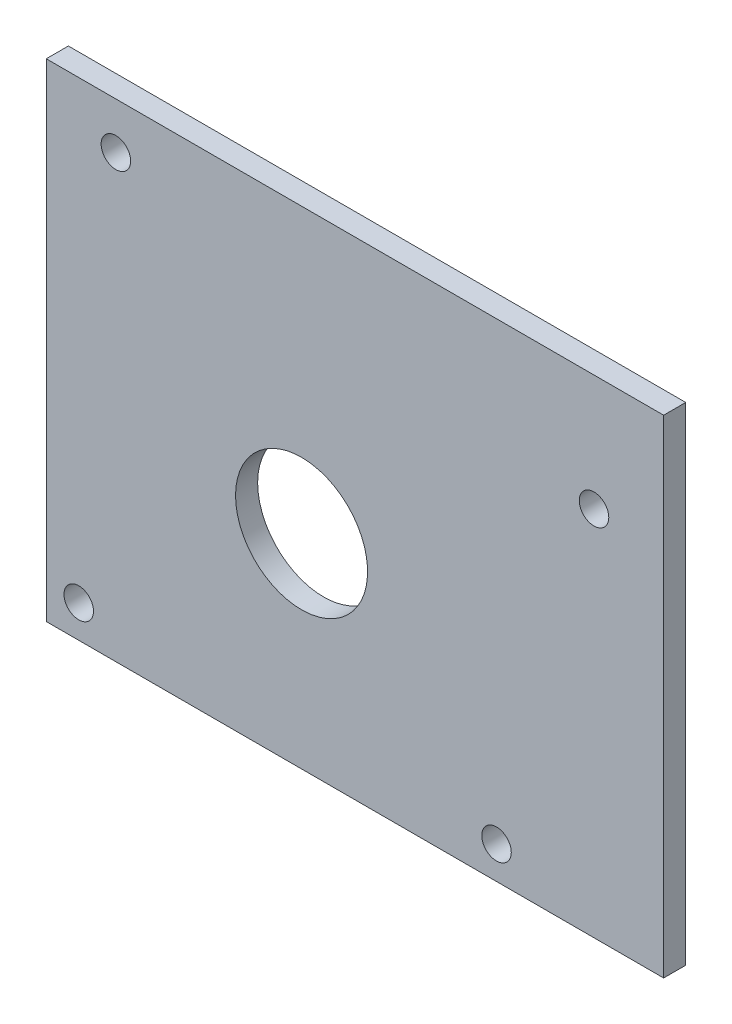
SolidWorks part; units mm, degrees
ref_plane "Front Plane" through (0, 0, 0) normal (0, 0, 1) x (1, 0, 0)
ref_plane "Top Plane" through (0, 0, 0) normal (0, 1, 0) x (1, 0, 0)
ref_plane "Right Plane" through (0, 0, 0) normal (1, 0, 0) x (0, 0, -1)
sketch "Sketch1" plane through (0, 0, 0) normal (0, 0, 1) x (1, 0, 0)
  line L0 (-85.0355, 74.3413) -> (-85.0355, -30.6587)
  line L1 (-85.0355, 74.3413) -> (47.9645, 74.3413)
  line L2 (-85.0355, -30.6587) -> (47.9645, -30.6587)
  line L3 (47.9645, 74.3413) -> (47.9645, -30.6587)
  circle A0 centre (-30.0355, 13.2613) radius 14.225
  dimension "D3" = 55
  dimension "D5" = 43.92
  dimension "D1" = 105
  dimension "D2" = 133
extrude "Boss-Extrude2" add sketch "Sketch1" along normal blind 4.7625
sketch "Sketch2" plane through (0, 0, 4.7625) normal (0, 0, 1) x (1, 0, 0)
  line L1 (-85.0355, 74.3413) -> (-85.0355, -30.6587) construction
  line L2 (47.9645, 74.3413) -> (-85.0355, 74.3413) construction
  line L3 (47.9645, -30.6587) -> (47.9645, 74.3413) construction
  line L4 (-85.0355, -30.6587) -> (47.9645, -30.6587) construction
  circle A1 centre (-70.0355, 64.3413) radius 3.18
  circle A2 centre (32.9645, 49.3413) radius 3.18
  circle A3 centre (11.9645, -23.6587) radius 3.18
  circle A4 centre (-78.0355, -23.6587) radius 3.18
  dimension "D1" = 15
  dimension "D3" = 15
  dimension "D5" = 7
  dimension "D7" = 7
  dimension "D2" = 10
  dimension "D4" = 25
  dimension "D6" = 36
extrude "Cut-Extrude1" cut sketch "Sketch2" against normal up to next
